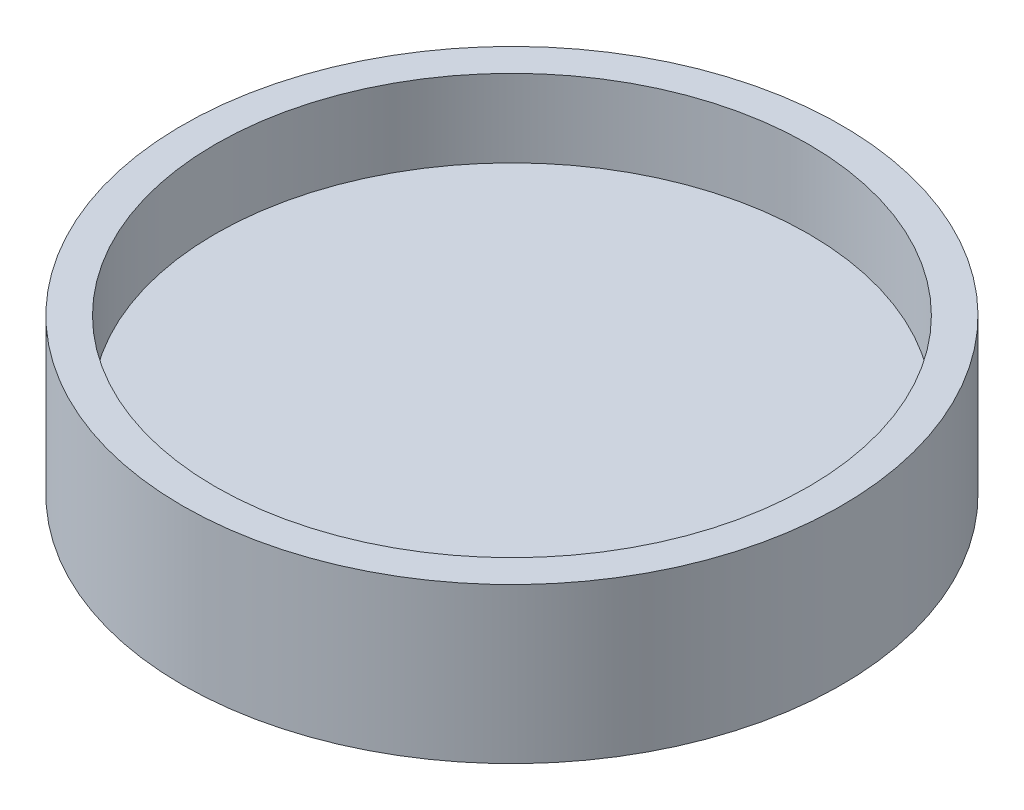
SolidWorks part; units mm, degrees
ref_plane "Front Plane" through (0, 0, 0) normal (0, 0, 1) x (1, 0, 0)
ref_plane "Top Plane" through (0, 0, 0) normal (0, 1, 0) x (1, 0, 0)
ref_plane "Right Plane" through (0, 0, 0) normal (1, 0, 0) x (0, 0, -1)
sketch "Sketch1" plane through (0, 0, 0) normal (0, 1, 0) x (1, 0, 0)
  circle A0 centre (0, 0) radius 8.5
  dimension "D1" = 17
extrude "Boss-Extrude3" add sketch "Sketch1" along normal blind 4
sketch "Sketch5" plane through (0, 4, 0) normal (0, 1, 0) x (1, 0, 0)
  circle A0 centre (0, 0) radius 7.65
  dimension "D1" = 15.3
extrude "Cut-Extrude2" cut sketch "Sketch5" against normal blind 2
